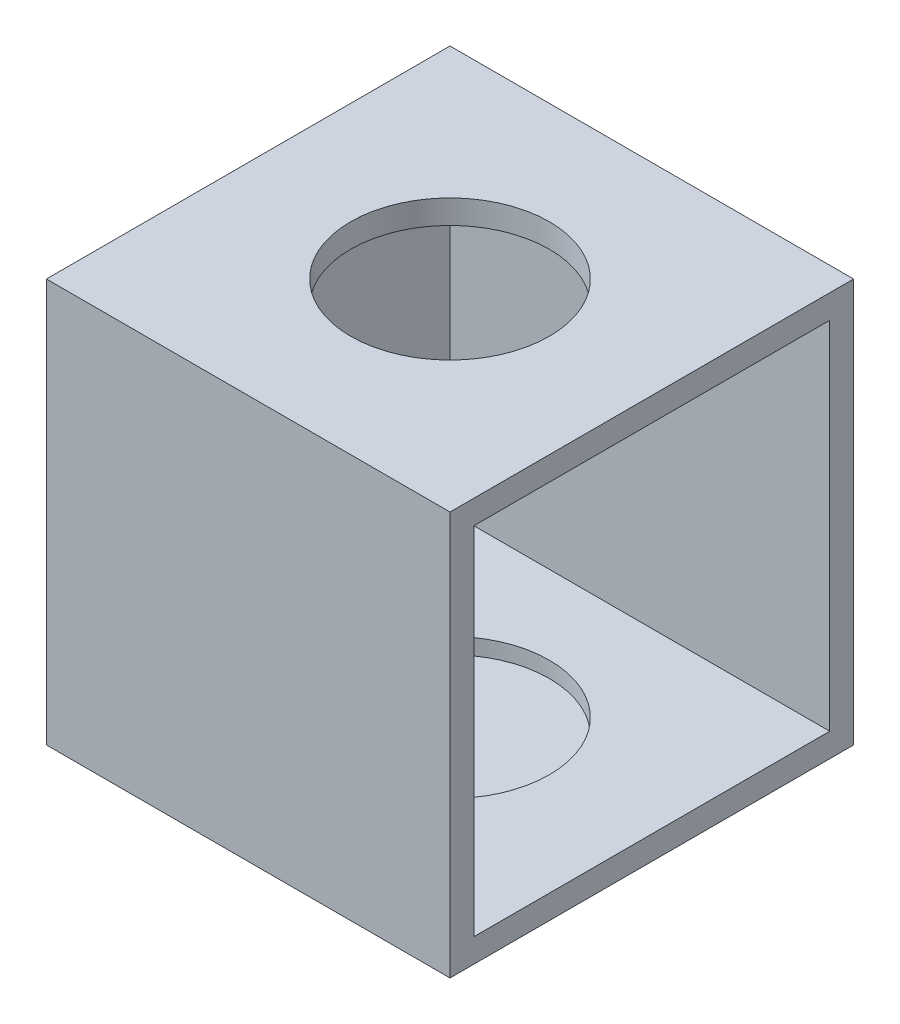
SolidWorks part; units mm, degrees
ref_plane "Front Plane" through (0, 0, 0) normal (0, 0, 1) x (1, 0, 0)
ref_plane "Top Plane" through (0, 0, 0) normal (0, 1, 0) x (1, 0, 0)
ref_plane "Right Plane" through (0, 0, 0) normal (1, 0, 0) x (0, 0, -1)
sketch "Sketch1" plane through (0, 0, 0) normal (0, 1, 0) x (1, 0, 0)
  line L1 (-25.4, 25.4) -> (25.4, 25.4)
  line L2 (-25.4, 25.4) -> (-25.4, -25.4)
  line L3 (-25.4, -25.4) -> (25.4, -25.4)
  line L4 (25.4, 25.4) -> (25.4, -25.4)
  line L5 (-25.4, 25.4) -> (25.4, -25.4) construction
  line L6 (-25.4, -25.4) -> (25.4, 25.4) construction
  point P0 (0, 0)
extrude "Boss-Extrude1" add sketch "Sketch1" along normal blind 50.8
shell "Shell1" thickness 3
sketch "Sketch2" plane through (-25.4, 0, 0) normal (-1, 0, 0) x (0, 0, 1)
  circle A1 centre (0, 25.4) radius 3.175
  dimension "D1" = 6.35
extrude "Cut-Extrude1" cut sketch "Sketch2" against normal blind 50.8
sketch "Sketch3" plane through (0, 50.8, 0) normal (0, 1, 0) x (1, 0, 0)
  circle A0 centre (0, 0) radius 12.5
extrude "Cut-Extrude2" cut sketch "Sketch3" against normal blind 49.8
sketch "Sketch4" plane through (-22.4, 0, 0) normal (1, 0, 0) x (0, 0, -1)
  line L1 (-12.5, 46.4427) -> (12.5, 46.4427)
  line L2 (-12.5, 46.4427) -> (-12.5, 40.4427)
  line L3 (-12.5, 40.4427) -> (12.5, 40.4427)
  line L4 (12.5, 46.4427) -> (12.5, 40.4427)
  line L5 (-12.5, 46.4427) -> (12.5, 40.4427) construction
  line L6 (-12.5, 40.4427) -> (12.5, 46.4427) construction
  point P0 (0, 43.4427)
extrude "Cut-Extrude3" cut sketch "Sketch4" against normal blind 49.8
